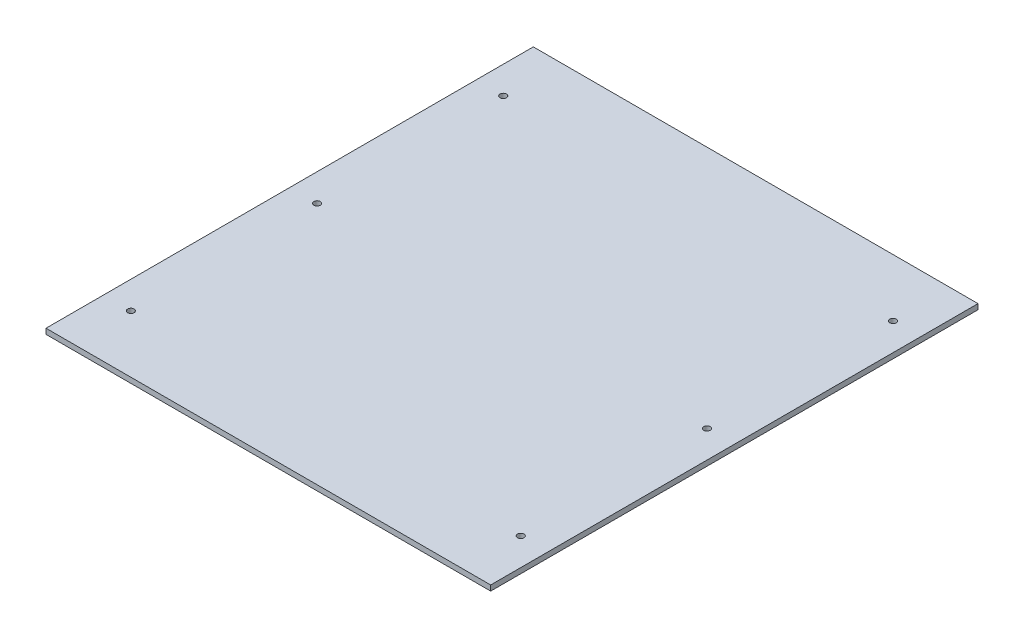
SolidWorks part; units mm, degrees
material "ABS PC"
ref_plane "Front Plane" through (0, 0, 0) normal (0, 0, 1) x (1, 0, 0)
ref_plane "Top Plane" through (0, 0, 0) normal (0, 1, 0) x (1, 0, 0)
ref_plane "Right Plane" through (0, 0, 0) normal (1, 0, 0) x (0, 0, -1)
sketch "Sketch1" plane through (0, 0, 0) normal (0, 1, 0) x (1, 0, 0)
  line L0 (231.775, 508) -> (231.775, 0) construction
  line L1 (0, 0) -> (463.55, 0)
  line L2 (0, 0) -> (0, 508)
  line L3 (0, 508) -> (463.55, 508)
  line L4 (463.55, 0) -> (463.55, 508)
  line L5 (28.575, 59.944) -> (28.575, 254) construction
  line L6 (28.575, 254) -> (28.575, 448.056) construction
  line L7 (434.975, 254) -> (434.975, 448.056) construction
  line L8 (434.975, 59.944) -> (434.975, 254) construction
  line L9 (28.575, 254) -> (231.775, 254) construction
  circle A0 centre (28.575, 59.944) radius 3.3782
  circle A1 centre (28.575, 254) radius 3.3782
  circle A2 centre (28.575, 448.056) radius 3.3782
  circle A3 centre (434.975, 448.056) radius 3.3782
  circle A4 centre (434.975, 254) radius 3.3782
  circle A5 centre (434.975, 59.944) radius 3.3782
  dimension "D3" = 6.7564
  dimension "D1" = 463.55
  dimension "D2" = 194.056
  dimension "D5" = 28.575
  dimension "D6" = 508
extrude "Boss-Extrude1" add sketch "Sketch1" along normal blind 5.588
fillet "Fillet1" [suppressed] radius 3.175
